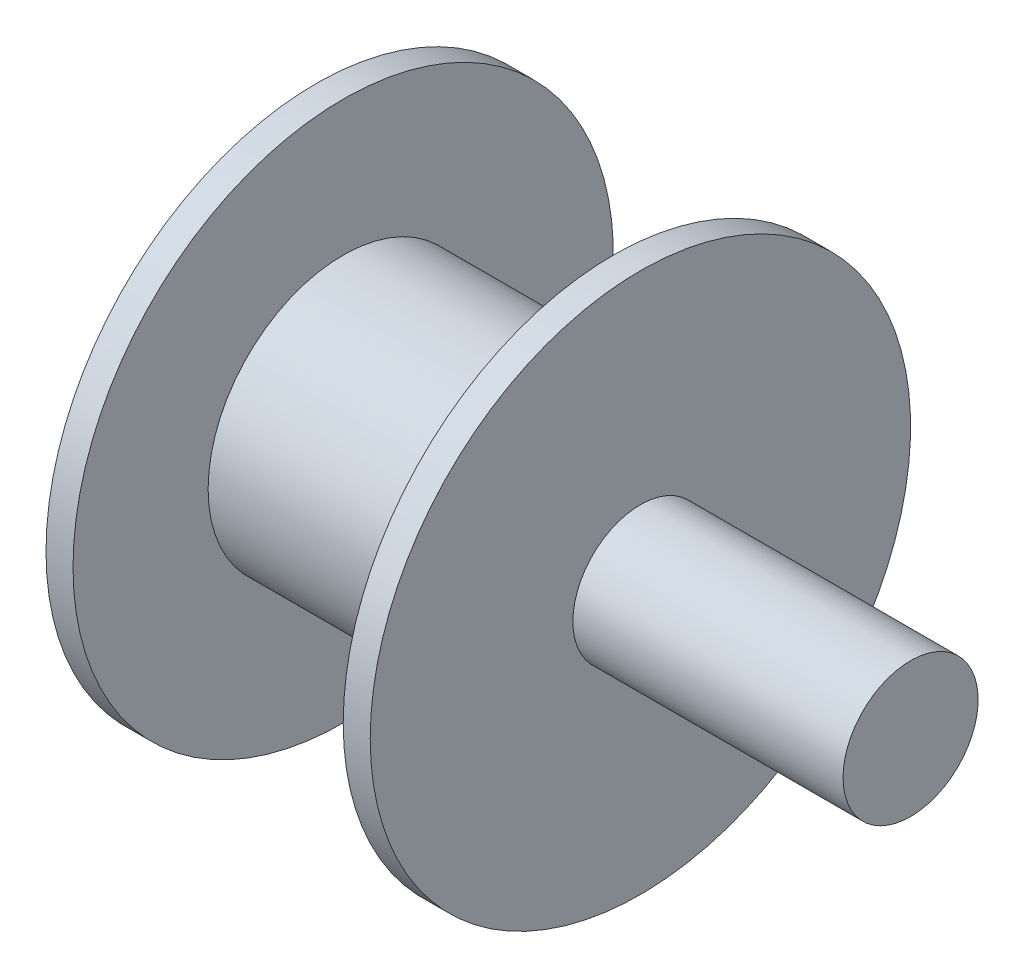
SolidWorks part; units mm, degrees
material "AISI 1020"
ref_plane "Front Plane" through (0, 0, 0) normal (0, 0, 1) x (1, 0, 0)
ref_plane "Top Plane" through (0, 0, 0) normal (0, 1, 0) x (1, 0, 0)
ref_plane "Right Plane" through (0, 0, 0) normal (1, 0, 0) x (0, 0, -1)
sketch "Sketch1" plane through (0, 0, 0) normal (0, 0, 1) x (1, 0, 0)
  line L0 (-571.7877, 0) -> (28017.5955, 0) construction
  line L1 (-50.9485, 0) -> (-50.9485, 20)
  line L2 (-50.9485, 20) -> (-48.9485, 20)
  line L3 (-48.9485, 20) -> (-48.9485, 10)
  line L4 (-48.9485, 10) -> (-28.9485, 10)
  line L5 (-28.9485, 10) -> (-28.9485, 20)
  line L6 (-28.9485, 20) -> (-26.9485, 20)
  line L9 (-26.9485, 5) -> (-6.9485, 5)
  line L10 (-6.9485, 5) -> (-6.9485, 0)
  line L11 (-6.9485, 0) -> (-50.9485, 0)
  line L12 (-26.9485, 20) -> (-26.9485, 5)
  dimension "D1" = 20
  dimension "D2" = 2
  dimension "D3" = 2
  dimension "D4" = 20
  dimension "D5" = 10
  dimension "D6" = 5
  dimension "D7" = 20
  dimension "D8" = 15
revolve "Revolve1" add sketch "Sketch1" angle 360 about L0
